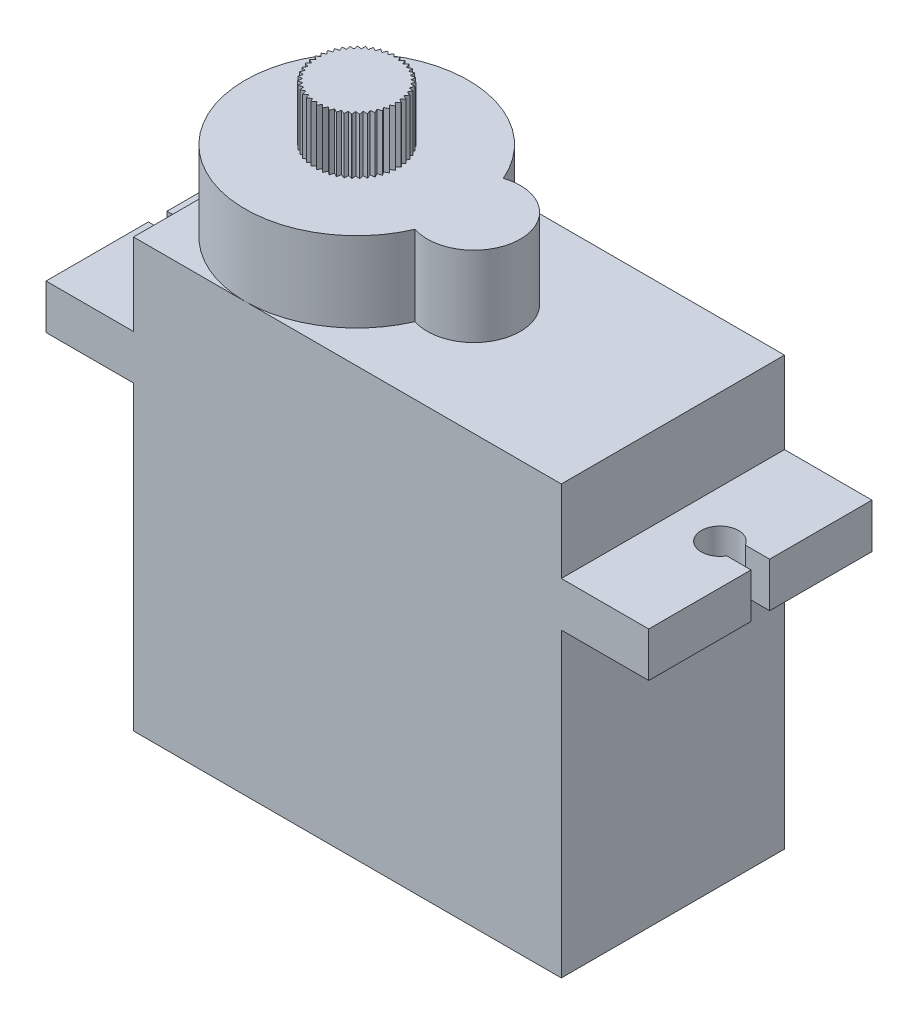
SolidWorks part; units mm, degrees
ref_plane "Front Plane" through (0, 0, 0) normal (0, 0, 1) x (1, 0, 0)
ref_plane "Top Plane" through (0, 0, 0) normal (0, 1, 0) x (1, 0, 0)
ref_plane "Right Plane" through (0, 0, 0) normal (1, 0, 0) x (0, 0, -1)
sketch "Sketch2" plane through (0, 0, 0) normal (0, 1, 0) x (1, 0, 0)
  line L1 (-11.5, -6) -> (11.5, -6)
  line L2 (-11.5, -6) -> (-11.5, 6)
  line L3 (-11.5, 6) -> (11.5, 6)
  line L4 (11.5, -6) -> (11.5, 6)
  line L5 (-11.5, -6) -> (11.5, 6) construction
  line L6 (-11.5, 6) -> (11.5, -6) construction
  point P0 (0, 0)
  dimension "D1" = 12
  dimension "D2" = 23
extrude "Boss-Extrude1" add sketch "Sketch2" against normal blind 23
sketch "Sketch3" plane through (0, 0, 0) normal (0, 1, 0) x (1, 0, 0)
  line L0 (11.5, 6) -> (-11.5, 6) construction
  line L1 (-16.2, -6) -> (16.2, -6)
  line L2 (-16.2, -6) -> (-16.2, 6)
  line L3 (-16.2, 6) -> (16.2, 6)
  line L4 (16.2, -6) -> (16.2, 6)
  line L5 (-16.2, -6) -> (16.2, 6) construction
  line L6 (-16.2, 6) -> (16.2, -6) construction
  line L8 (-15.5843, 0.5) -> (-16.2, 0.5)
  line L9 (-15.5843, 0.5) -> (-15.5843, -0.5)
  line L10 (-15.5843, -0.5) -> (-16.2, -0.5)
  line L11 (-16.2, 0.5) -> (-16.2, -0.5)
  line L12 (16.2, 0.5) -> (14.8944, 0.5)
  line L13 (16.2, 0.5) -> (16.2, -0.5)
  line L14 (16.2, -0.5) -> (14.8944, -0.5)
  line L15 (14.8944, 0.5) -> (14.8944, -0.5)
  circle A0 centre (-14.7183, 0) radius 1
  circle A1 centre (14.0284, 0) radius 1
  point P0 (0, 0)
  line M15 (11.5, -6) -> (11.5, 6)
  line M17 (-11.5, 6) -> (-11.5, -6)
  dimension "D2" = 2
  dimension "D1" = 32.4
  dimension "D3" = 1
  dimension "D4" = 1
extrude "Boss-Extrude2" add sketch "Sketch3" against normal blind 2.4 from offset 4.4 contours A0 L10 L2 L1 L3 L8 M17 | A1 L12 L4 L3 L1 L14 M15 offset against normal yes
sketch "Sketch4" plane through (0, 0, 0) normal (0, 1, 0) x (1, 0, 0)
  line L0 (-11.5, 6) -> (-11.5, -6) construction
  line L1 (11.5, 6) -> (-11.5, 6) construction
  line L2 (3.3, 0) -> (-11.5, 0) construction
  circle A0 centre (-5.5, 0) radius 6
  circle A1 centre (0.8, 0) radius 2.5
  dimension "D1" = 14.8
  dimension "D2" = 5
extrude "Boss-Extrude3" add sketch "Sketch4" along normal blind 4.3 contours L2 A1 A0 | A1 L2 A0 | A1 L2 A0 | L2 A1 A0 | L2 A0 A1 | A0 L2 A1
sketch "Sketch5" plane through (0, 4.3, 0) normal (0, 1, 0) x (1, 0, 0)
  line L0 (-3.255, -0.15) -> (-3.4372, 0)
  line L1 (-3.4372, 0) -> (-3.255, 0.15)
  line L2 (-3.295, -0.4479) -> (-3.4556, -0.2749)
  line L3 (-3.4556, -0.2749) -> (-3.255, -0.1506)
  line L4 (-3.3744, -0.7378) -> (-3.5105, -0.545)
  line L5 (-3.5105, -0.545) -> (-3.2951, -0.4484)
  line L6 (-3.4917, -1.0145) -> (-3.6009, -0.8053)
  line L7 (-3.6009, -0.8053) -> (-3.3746, -0.7383)
  line L8 (-3.6448, -1.2731) -> (-3.7252, -1.0512)
  line L9 (-3.7252, -1.0512) -> (-3.492, -1.015)
  line L10 (-3.8311, -1.5091) -> (-3.8811, -1.2784)
  line L11 (-3.8811, -1.2784) -> (-3.6452, -1.2736)
  line L12 (-4.0471, -1.718) -> (-4.0659, -1.4828)
  line L13 (-4.0659, -1.4828) -> (-3.8315, -1.5095)
  line L14 (-4.2891, -1.8964) -> (-4.2764, -1.6607)
  line L15 (-4.2764, -1.6607) -> (-4.0476, -1.7184)
  line L16 (-4.5526, -2.0408) -> (-4.5086, -1.809)
  line L17 (-4.5086, -1.809) -> (-4.2896, -1.8967)
  line L18 (-4.8331, -2.1489) -> (-4.7586, -1.925)
  line L19 (-4.7586, -1.925) -> (-4.5532, -2.0411)
  line L20 (-5.1255, -2.2186) -> (-5.0218, -2.0066)
  line L21 (-5.0218, -2.0066) -> (-4.8337, -2.1491)
  line L22 (-5.4245, -2.2487) -> (-5.2935, -2.0525)
  line L23 (-5.2935, -2.0525) -> (-5.126, -2.2187)
  line L24 (-5.7249, -2.2387) -> (-5.5689, -2.0617)
  line L25 (-5.5689, -2.0617) -> (-5.4251, -2.2488)
  line L26 (-6.0213, -2.1888) -> (-5.8431, -2.0341)
  line L27 (-5.8431, -2.0341) -> (-5.7255, -2.2387)
  line L28 (-6.3084, -2.0998) -> (-6.1112, -1.9702)
  line L29 (-6.1112, -1.9702) -> (-6.0219, -2.1886)
  line L30 (-6.5811, -1.9733) -> (-6.3683, -1.8712)
  line L31 (-6.3683, -1.8712) -> (-6.3089, -2.0996)
  line L32 (-6.8344, -1.8116) -> (-6.61, -1.7387)
  line L33 (-6.61, -1.7387) -> (-6.5816, -1.973)
  line L34 (-7.064, -1.6176) -> (-6.8318, -1.5753)
  line L35 (-6.8318, -1.5753) -> (-6.8349, -1.8112)
  line L36 (-7.2656, -1.3947) -> (-7.0299, -1.3837)
  line L37 (-7.0299, -1.3837) -> (-7.0644, -1.6172)
  line L38 (-7.4358, -1.1469) -> (-7.2007, -1.1674)
  line L39 (-7.2007, -1.1674) -> (-7.266, -1.3942)
  line L40 (-7.5714, -0.8786) -> (-7.3411, -0.9304)
  line L41 (-7.3411, -0.9304) -> (-7.436, -1.1464)
  line L42 (-7.67, -0.5947) -> (-7.4487, -0.6767)
  line L43 (-7.4487, -0.6767) -> (-7.5716, -0.8781)
  line L44 (-7.7299, -0.3002) -> (-7.5215, -0.4109)
  line L45 (-7.5215, -0.4109) -> (-7.6701, -0.5942)
  line L46 (-7.75, -0.0003) -> (-7.5582, -0.1378)
  line L47 (-7.5582, -0.1378) -> (-7.73, -0.2996)
  line L48 (-7.73, 0.2996) -> (-7.5582, 0.1378)
  line L49 (-7.5582, 0.1378) -> (-7.75, 0.0003)
  line L50 (-7.6701, 0.5942) -> (-7.5215, 0.4109)
  line L51 (-7.5215, 0.4109) -> (-7.7299, 0.3002)
  line L52 (-7.5716, 0.8781) -> (-7.4487, 0.6767)
  line L53 (-7.4487, 0.6767) -> (-7.67, 0.5947)
  line L54 (-7.436, 1.1464) -> (-7.3411, 0.9304)
  line L55 (-7.3411, 0.9304) -> (-7.5714, 0.8786)
  line L56 (-7.266, 1.3942) -> (-7.2007, 1.1674)
  line L57 (-7.2007, 1.1674) -> (-7.4358, 1.1469)
  line L58 (-7.0644, 1.6172) -> (-7.0299, 1.3837)
  line L59 (-7.0299, 1.3837) -> (-7.2656, 1.3947)
  line L60 (-6.8349, 1.8112) -> (-6.8318, 1.5753)
  line L61 (-6.8318, 1.5753) -> (-7.064, 1.6176)
  line L62 (-6.5816, 1.973) -> (-6.61, 1.7387)
  line L63 (-6.61, 1.7387) -> (-6.8344, 1.8116)
  line L64 (-6.3089, 2.0996) -> (-6.3683, 1.8712)
  line L65 (-6.3683, 1.8712) -> (-6.5811, 1.9733)
  line L66 (-6.0219, 2.1886) -> (-6.1112, 1.9702)
  line L67 (-6.1112, 1.9702) -> (-6.3084, 2.0998)
  line L68 (-5.7255, 2.2387) -> (-5.8431, 2.0341)
  line L69 (-5.8431, 2.0341) -> (-6.0213, 2.1888)
  line L70 (-5.4251, 2.2488) -> (-5.5689, 2.0617)
  line L71 (-5.5689, 2.0617) -> (-5.7249, 2.2387)
  line L72 (-5.126, 2.2187) -> (-5.2935, 2.0525)
  line L73 (-5.2935, 2.0525) -> (-5.4245, 2.2487)
  line L74 (-4.8337, 2.1491) -> (-5.0218, 2.0066)
  line L75 (-5.0218, 2.0066) -> (-5.1255, 2.2186)
  line L76 (-4.5532, 2.0411) -> (-4.7586, 1.925)
  line L77 (-4.7586, 1.925) -> (-4.8331, 2.1489)
  line L78 (-4.2896, 1.8967) -> (-4.5086, 1.809)
  line L79 (-4.5086, 1.809) -> (-4.5526, 2.0408)
  line L80 (-4.0476, 1.7184) -> (-4.2764, 1.6607)
  line L81 (-4.2764, 1.6607) -> (-4.2891, 1.8964)
  line L82 (-3.8315, 1.5095) -> (-4.0659, 1.4828)
  line L83 (-4.0659, 1.4828) -> (-4.0471, 1.718)
  line L84 (-3.6452, 1.2736) -> (-3.8811, 1.2784)
  line L85 (-3.8811, 1.2784) -> (-3.8311, 1.5091)
  line L86 (-3.492, 1.015) -> (-3.7252, 1.0512)
  line L87 (-3.7252, 1.0512) -> (-3.6448, 1.2731)
  line L88 (-3.3746, 0.7383) -> (-3.6009, 0.8053)
  line L89 (-3.6009, 0.8053) -> (-3.4917, 1.0145)
  line L90 (-3.2951, 0.4484) -> (-3.5105, 0.545)
  line L91 (-3.5105, 0.545) -> (-3.3744, 0.7378)
  line L92 (-3.255, 0.1506) -> (-3.4556, 0.2749)
  line L93 (-3.4556, 0.2749) -> (-3.295, 0.4479)
  circle A0 centre (-5.5, 0) radius 2.25
  point P146 (-5.5, 0)
  dimension "D1" = 4.5
  dimension "D2" = 0.15
  dimension "D3" = 47
extrude "Boss-Extrude4" add sketch "Sketch5" along normal blind 3 contours L25 A0 L22 L23 L20 L21 L18 L19 L16 L17 L14 L15 L12 L13 L10 L11 L8 L9 L6 L7 L4 L5 L2 L3 L0 L1 L92 L93 L90 L91 L88 L89 L86 L87 L84
sketch "Sketch6" plane through (-11.5, 0, 0) normal (-1, 0, 0) x (0, 0, 1)
  line L0 (-6, -23) -> (6, -23) construction
  line L1 (-1.5, -17) -> (1.5, -17)
  line L2 (-1.5, -17) -> (-1.5, -18)
  line L3 (-1.5, -18) -> (1.5, -18)
  line L4 (1.5, -17) -> (1.5, -18)
  point P7 (0, -17)
  dimension "D1" = 5
  dimension "D2" = 3
  dimension "D3" = 1
extrude "Boss-Extrude5" add sketch "Sketch6" along normal blind 3
